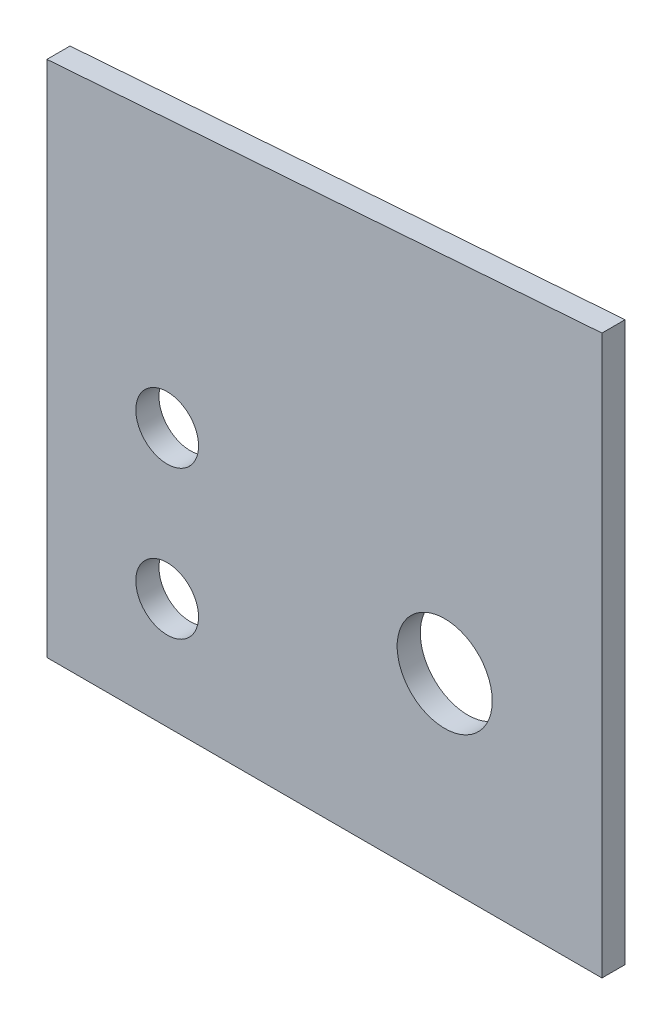
SolidWorks part; units mm, degrees
material "AISI 4130 Steel, annealed at 865C"
ref_plane "Front Plane" through (0, 0, 0) normal (0, 0, 1) x (1, 0, 0)
ref_plane "Top Plane" through (0, 0, 0) normal (0, 1, 0) x (1, 0, 0)
ref_plane "Right Plane" through (0, 0, 0) normal (1, 0, 0) x (0, 0, -1)
sketch "Sketch1" plane through (0, 0, 0) normal (0, 0, 1) x (1, 0, 0)
  line L0 (0, 25.4) -> (38.1, 25.4)
  line L1 (0, 0) -> (38.1, 0)
  line L2 (0, 0) -> (0, 35.56)
  line L3 (0, 35.56) -> (38.1, 35.56)
  line L4 (38.1, 0) -> (38.1, 35.56)
  line L5 (16.51, 25.4) -> (16.51, 0)
  line L6 (8.255, 15.6274) -> (8.255, 9.7726) construction
  line L7 (8.255, 5.4673) -> (8.255, 0) construction
  line L8 (8.255, 19.9326) -> (8.255, 25.4) construction
  line L9 (6.1024, 17.78) -> (0, 17.78) construction
  line L10 (0, 35.56) -> (38.1, 38.3404)
  line L11 (38.1, 38.3404) -> (38.1, 35.56)
  circle A0 centre (8.255, 17.78) radius 2.1526
  circle A1 centre (8.255, 7.62) radius 2.1527
  circle A2 centre (27.305, 12.7) radius 3.2639
  point P22 (8.255, 12.7)
  dimension "D10" = 4.3053
  dimension "D12" = 6.5278
  dimension "D15" = 4.174
  dimension "D1" = 35.56
  dimension "D2" = 38.1
  dimension "D3" = 7.62
  dimension "D4" = 7.62
  dimension "D5" = 25.4
  dimension "D7" = 8.255
  dimension "D8" = 25.4
  dimension "D11" = 21.59
  dimension "D13" = 10.795
  dimension "D14" = 12.7
  dimension "D16" = 38.3404
extrude "Boss-Extrude1" add sketch "Sketch1" along normal blind 1.5875 contours L0 L4 L3 L2 | L5 L0 L2 L1 A1 A0 | L0 L5 L1 L4 A2 | L11 L10 L3
